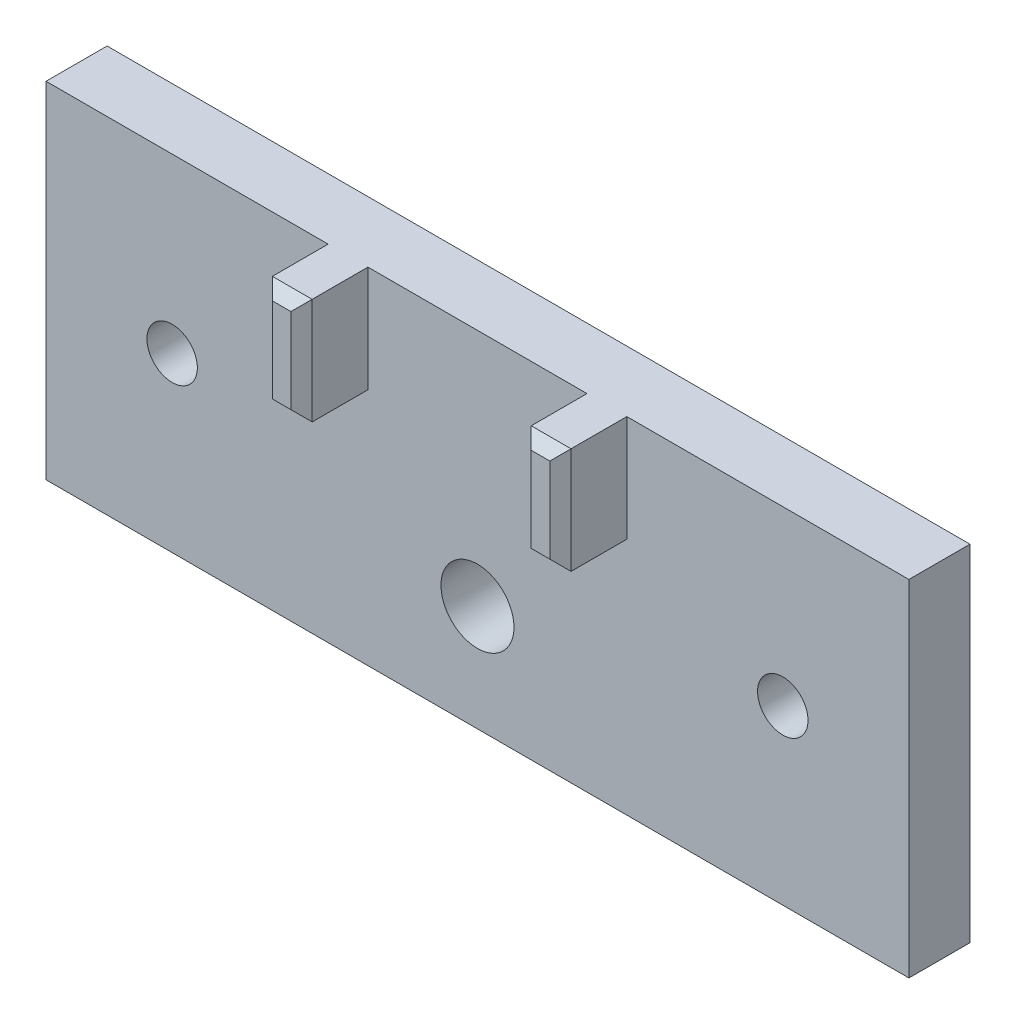
SolidWorks part; units mm, degrees
ref_plane "Top Plane" through (0, 0, 0) normal (0, 0, 1) x (1, 0, 0)
ref_plane "Front Plane" through (0, 0, 0) normal (0, 1, 0) x (1, 0, 0)
ref_plane "Right Plane" through (0, 0, 0) normal (1, 0, 0) x (0, 0, -1)
sketch "Sketch1" plane through (0, 0, 0) normal (0, 0, 1) x (1, 0, 0)
  line L1 (0, 0) -> (65, 0)
  line L2 (0, 0) -> (0, 26)
  line L3 (0, 26) -> (65, 26)
  line L4 (65, 0) -> (65, 26)
  dimension "D1" = 65
  dimension "D2" = 26
extrude "Boss-Extrude1" add sketch "Sketch1" along normal blind 5
sketch "Sketch2" plane through (0, 0, 5) normal (0, 0, 1) x (1, 0, 0)
  line L0 (0, 26) -> (0, 0) construction
  line L1 (0, 0) -> (65, 0) construction
  circle A0 centre (32.5, 8) radius 2.75
  dimension "D1" = 5.5
  dimension "D3" = 8
  dimension "D2" = 32.5
extrude "Cut-Extrude1" cut sketch "Sketch2" against normal blind 5
sketch "Sketch3" plane through (0, 0, 5) normal (0, 0, 1) x (1, 0, 0)
  line L0 (65, 26) -> (0, 26) construction
  line L1 (21.25, 26) -> (24.25, 26)
  line L2 (21.25, 26) -> (21.25, 18)
  line L3 (21.25, 18) -> (24.25, 18)
  line L4 (24.25, 26) -> (24.25, 18)
  line L6 (40.75, 26) -> (43.75, 26)
  line L7 (40.75, 26) -> (40.75, 18)
  line L8 (40.75, 18) -> (43.75, 18)
  line L9 (43.75, 26) -> (43.75, 18)
  circle A0 centre (32.5, 8) radius 2.75 construction
  dimension "D1" = 10
  dimension "D2" = 22.5
  dimension "D3" = 3
  dimension "D4" = 11.25
extrude "Boss-Extrude2" add sketch "Sketch3" along normal blind 5
chamfer "Chamfer1" distance 0.8 angle 45 8 edges at (42.25, 26, 10) (43.75, 22, 10) (42.25, 18, 10) (40.75, 22, 10) (22.75, 26, 10) (24.25, 22, 10) (22.75, 18, 10) (21.25, 22, 10)
sketch "Sketch4" plane through (0, 0, 0) normal (0, 0, -1) x (-1, 0, 0)
  line L1 (0, 0) -> (-65, 0) construction
  line L2 (-65, 0) -> (-65, 26) construction
  circle A0 centre (-55.5, 13) radius 1.9
  circle A1 centre (-9.5, 13) radius 1.9
  point P4 (0, 0)
  dimension "D2" = 13
  dimension "D3" = 9.5
  dimension "D4" = 3.8
  dimension "D1" = 46
extrude "Cut-Extrude2" cut sketch "Sketch4" against normal blind 5
chamfer "Chamfer2" distance 0.4 angle 45 7 edges at (32.5, 0, 0) (65, 13, 0) (32.5, 26, 0) (0, 13, 0) (35.25, 8, 0) (7.6, 13, 0) (53.6, 13, 0)
